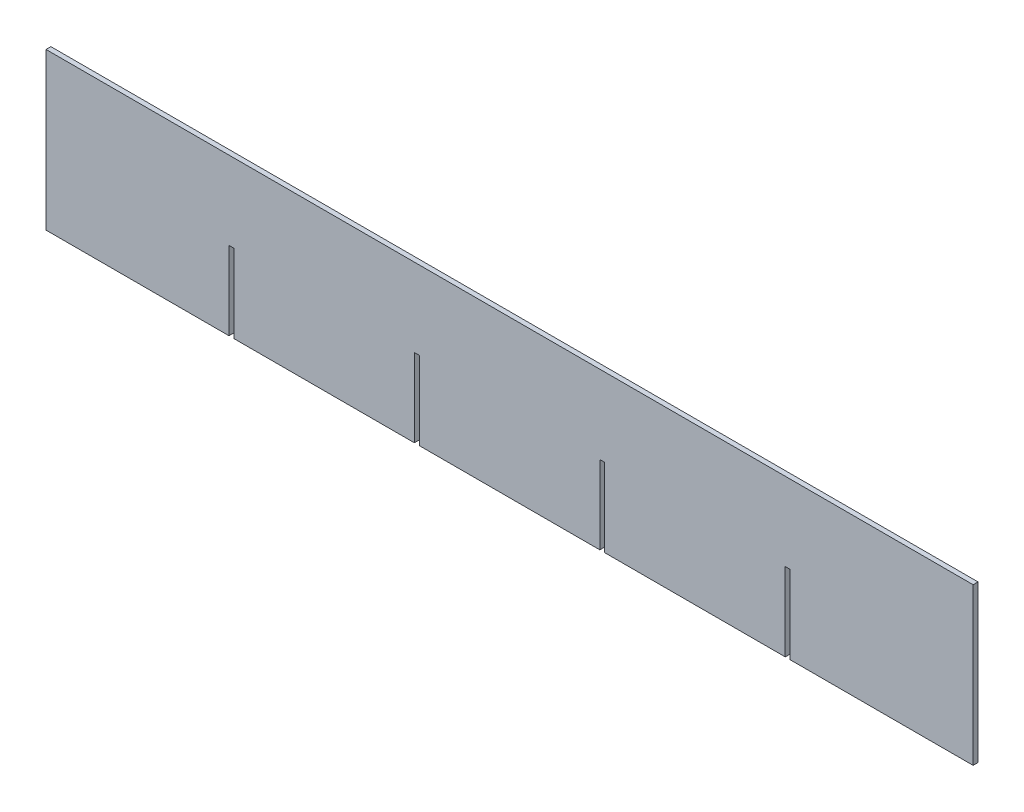
SolidWorks part; units mm, degrees
material "Mahogany"
ref_plane "Front Plane" through (0, 0, 0) normal (0, 0, 1) x (1, 0, 0)
ref_plane "Top Plane" through (0, 0, 0) normal (0, 1, 0) x (1, 0, 0)
ref_plane "Right Plane" through (0, 0, 0) normal (1, 0, 0) x (0, 0, -1)
sketch "Sketch1" plane through (0, 0, 0) normal (0, 0, 1) x (1, 0, 0)
  line L0 (-142.2, -40) -> (-142.2, 40) construction
  line L1 (-237, -40) -> (237, -40) construction
  line L2 (-237, -40) -> (-237, 40) construction
  line L3 (-237, 40) -> (237, 40) construction
  line L4 (237, -40) -> (237, 40) construction
  line L5 (-237, -40) -> (237, 40) construction
  line L6 (-237, 40) -> (237, -40) construction
  line L7 (-47.4, -40) -> (-47.4, 40) construction
  line L8 (47.4, -40) -> (47.4, 40) construction
  line L9 (142.2, -40) -> (142.2, 40) construction
  line L10 (-48.65, -40) -> (-48.65, 0)
  line L11 (-143.45, -40) -> (-140.95, -40) construction
  line L12 (-143.45, -40) -> (-143.45, 0)
  line L13 (-143.45, 0) -> (-140.95, 0)
  line L14 (-140.95, -40) -> (-140.95, 0)
  line L15 (-143.45, -40) -> (-140.95, 0) construction
  line L16 (-143.45, 0) -> (-140.95, -40) construction
  line L17 (-48.65, 0) -> (-46.15, 0)
  line L18 (-46.15, -40) -> (-46.15, 0)
  line L19 (46.15, -40) -> (46.15, 0)
  line L20 (46.15, 0) -> (48.65, 0)
  line L21 (48.65, -40) -> (48.65, 0)
  line L22 (140.95, -40) -> (140.95, 0)
  line L23 (140.95, 0) -> (143.45, 0)
  line L24 (143.45, -40) -> (143.45, 0)
  line L25 (-143.45, -40) -> (-237, -40)
  line L26 (-237, -40) -> (-237, 40)
  line L27 (-237, 40) -> (237, 40)
  line L28 (237, 40) -> (237, -40)
  line L29 (237, -40) -> (143.45, -40)
  line L30 (140.95, -40) -> (48.65, -40)
  line L31 (46.15, -40) -> (-46.15, -40)
  line L32 (-48.65, -40) -> (-140.95, -40)
  point P0 (0, 0)
  point P8 (-142.2, -20)
  point P19 (-142.2, 0)
  point P20 (-47.4, 0)
  dimension "D1" = 474
  dimension "D2" = 80
  dimension "D3" = 94.8
  dimension "D4" = 4
  dimension "D5" = 94.8
  dimension "D6" = 2.5
  dimension "D7" = 4
extrude "Boss-Extrude1" add sketch "Sketch1" along normal mid plane 2.5
